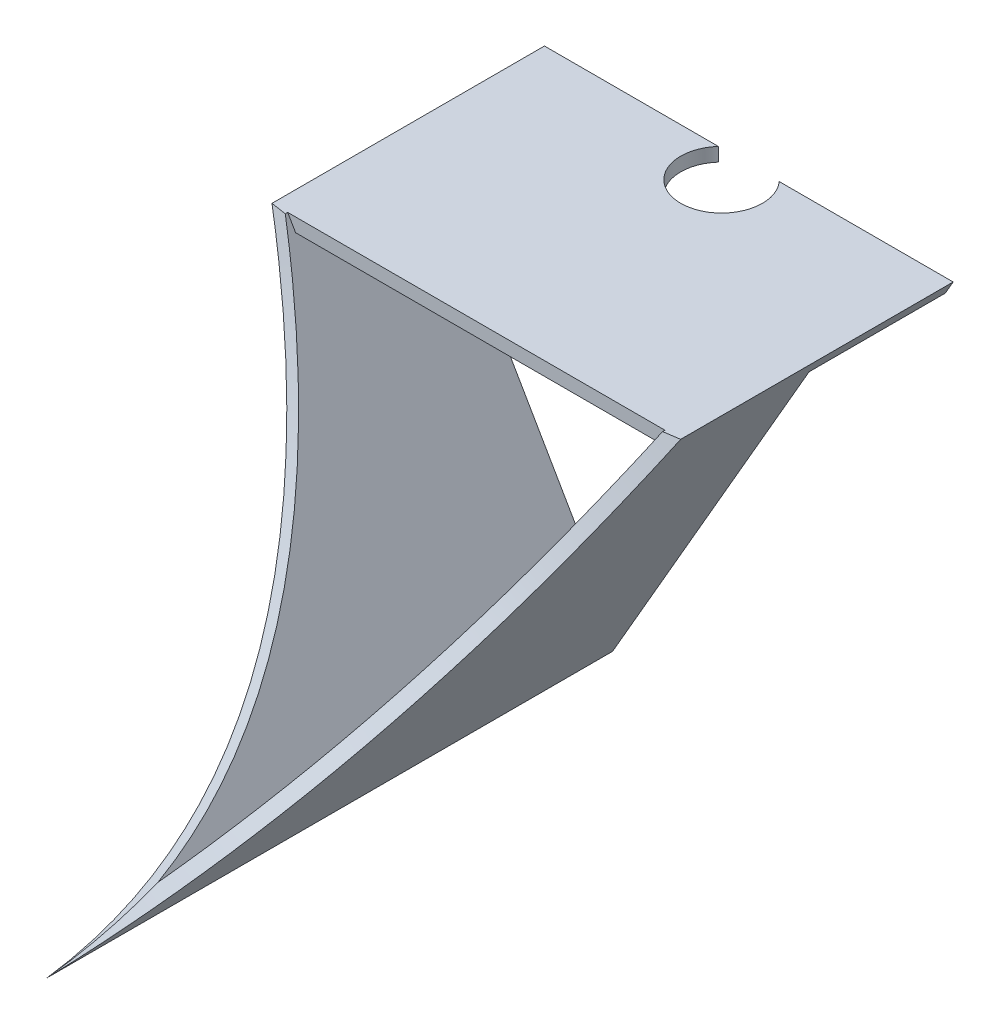
SolidWorks part; units mm, degrees
ref_plane "Front Plane" through (0, 0, 0) normal (0, 0, 1) x (1, 0, 0)
ref_plane "Top Plane" through (0, 0, 0) normal (0, 1, 0) x (1, 0, 0)
ref_plane "Right Plane" through (0, 0, 0) normal (1, 0, 0) x (0, 0, -1)
sketch "Sketch1" plane through (0, 0, 0) normal (0, 0, 1) x (1, 0, 0)
  line L0 (-13.2679, 0) -> (13.2679, 0)
  line L1 (13.2679, 0) -> (0, -22.9808)
  line L2 (-13.2679, 0) -> (0, -22.9808)
  line L3 (-15, 1) -> (15, 1)
  line L4 (15, 1) -> (0, -24.9808)
  line L5 (-15, 1) -> (0, -24.9808)
  point P4 (0, 0)
  dimension "D1" = 30
  dimension "D2" = 60
  dimension "D3" = 1
extrude "Boss-Extrude1" add sketch "Sketch1" along normal blind 60
sketch "Sketch4" plane through (10.817, -6.2452, 0) normal (0.866, -0.5, 0) x (0, 0, -1)
  line L0 (-60, -21.634) -> (-29.8865, -24.2407) construction
  line L2 (-29.8865, -24.2407) -> (-20, 8.366) construction
  line L3 (-60, 8.366) -> (0, 8.366) construction
  line L4 (-60, 8.366) -> (-60, -21.634)
  line L5 (-60, 8.366) -> (-20, 8.366)
  spline S0 degree 2 poles (-60, -21.634) (-29.8865, -24.2407) (-20, 8.366) knots 0 0 0 1 1 1
  dimension "D3" = 55
  dimension "D1" = 20
  dimension "D2" = 30
extrude "Cut-Extrude2" cut sketch "Sketch4" against normal blind 1
mirror "Mirror1" about plane through (0, 0, 0) normal (1, 0, 0) of "Cut-Extrude2"
sketch "Sketch5" plane through (0, 0, 60) normal (0, 0, 1) x (1, 0, 0)
  line L0 (-13.8453, 1) -> (13.8453, 1)
  line L1 (13.8453, 1) -> (13.2679, 0)
  line L2 (13.2679, 0) -> (-13.2679, 0)
  line L3 (-13.2679, 0) -> (-13.8453, 1)
extrude "Cut-Extrude3" cut sketch "Sketch5" against normal blind 40
sketch "Sketch8" plane through (0, 0, 0) normal (0, 0, -1) x (-1, 0, 0)
  line L0 (-15.8722, 0) -> (15.8722, 0)
  line L2 (-15.8722, 0) -> (0, -24.9808)
  line L3 (0, -24.9808) -> (15.8722, 0)
  point P3 (0, 0)
extrude "Cut-Extrude4" cut sketch "Sketch8" against normal blind 10
sketch "Sketch9" plane through (0, 1, 0) normal (0, 1, 0) x (1, 0, 0)
  line L0 (15, 0) -> (-15, 0) construction
  line L1 (15, -20) -> (15, 0) construction
  circle A0 centre (0, -2) radius 3
  dimension "D1" = 6
  dimension "D3" = 15
  dimension "D2" = 2
extrude "Cut-Extrude5" cut sketch "Sketch9" against normal blind 1
